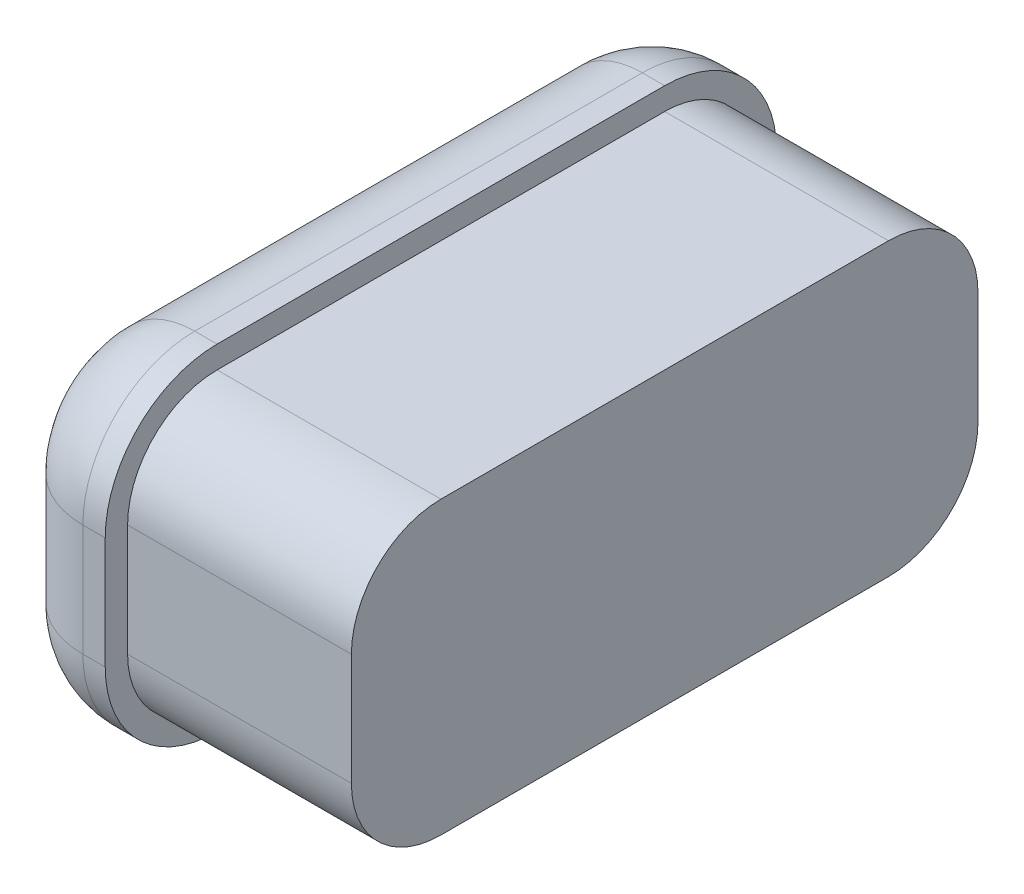
SolidWorks part; units mm, degrees
material "ABS"
ref_plane "Спереди" through (0, 0, 0) normal (0, 0, 1) x (1, 0, 0)
ref_plane "Сверху" through (0, 0, 0) normal (0, 1, 0) x (1, 0, 0)
ref_plane "Справа" through (0, 0, 0) normal (1, 0, 0) x (0, 0, -1)
sketch "Эскиз1" plane through (0, 0, 0) normal (1, 0, 0) x (0, 0, -1)
  line L1 (15, -7.5) -> (-15, -7.5)
  line L2 (15, -7.5) -> (15, 7.5)
  line L3 (15, 7.5) -> (-15, 7.5)
  line L4 (-15, -7.5) -> (-15, 7.5)
  line L5 (15, -7.5) -> (-15, 7.5) construction
  line L6 (15, 7.5) -> (-15, -7.5) construction
  point P0 (0, 0)
  dimension "D1" = 30
  dimension "D2" = 15
extrude "Бобышка-Вытянуть1" add sketch "Эскиз1" along normal blind 5
sketch "Эскиз2" plane through (5, 0, 0) normal (1, 0, 0) x (0, 0, -1)
  line L1 (14, -6.5) -> (-14, -6.5)
  line L2 (14, -6.5) -> (14, 6.5)
  line L3 (14, 6.5) -> (-14, 6.5)
  line L4 (-14, -6.5) -> (-14, 6.5)
  line L5 (14, -6.5) -> (-14, 6.5) construction
  line L6 (14, 6.5) -> (-14, -6.5) construction
  point P0 (0, 0)
  dimension "D1" = 28
  dimension "D2" = 13
extrude "Бобышка-Вытянуть2" add sketch "Эскиз2" along normal blind 10
fillet "Скругление2" radius 4 4 edges at (10, -6.5, -14) (10, 6.5, -14) (10, -6.5, 14) (10, 6.5, 14)
fillet "Скругление1" radius 5 4 edges at (2.5, 7.5, -15) (2.5, -7.5, -15) (2.5, -7.5, 15) (2.5, 7.5, 15)
fillet "Скругление3" radius 4 8 edges at (0, 6.0355, 13.5355) (0, 0, 15) (0, -6.0355, 13.5355) (0, -7.5, 0) (0, -6.0355, -13.5355) (0, 0, -15) (0, 6.0355, -13.5355) (0, 7.5, 0)
